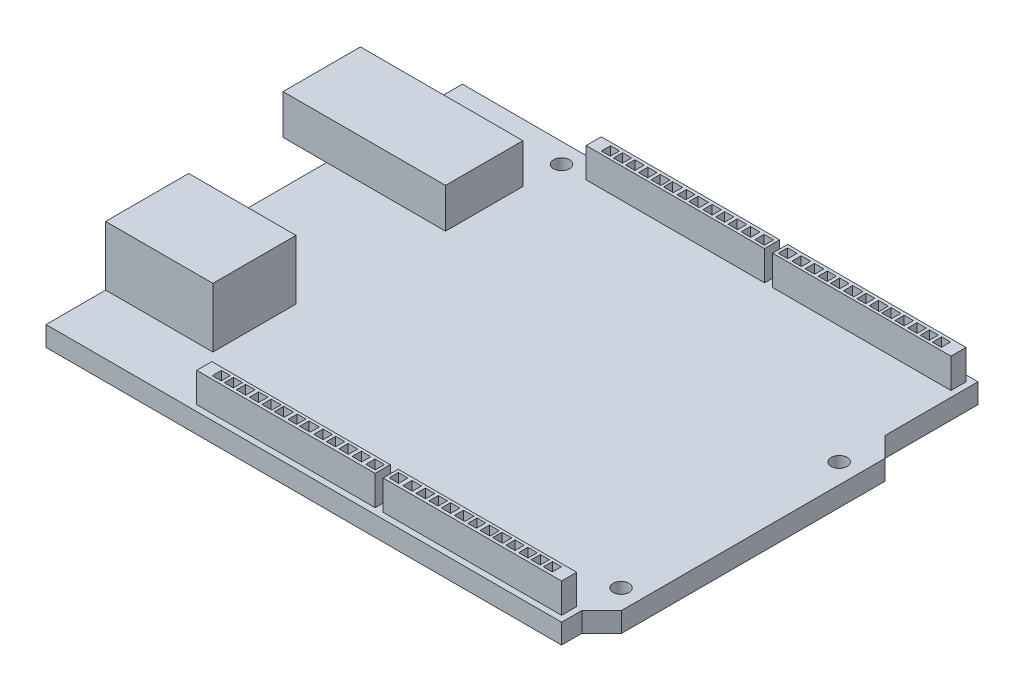
SolidWorks part; units mm, degrees
ref_plane "Front Plane" through (0, 0, 0) normal (0, 0, 1) x (1, 0, 0)
ref_plane "Top Plane" through (0, 0, 0) normal (0, 1, 0) x (1, 0, 0)
ref_plane "Right Plane" through (0, 0, 0) normal (1, 0, 0) x (0, 0, -1)
sketch "Sketch1" plane through (0, 0, 0) normal (0, 1, 0) x (1, 0, 0)
  line L0 (66.04, 53.34) -> (66.04, 0) construction
  line L1 (0, 0) -> (66.04, 0)
  line L2 (0, 0) -> (0, 53.34)
  line L3 (0, 53.34) -> (66.04, 53.34)
  line L4 (68.58, 5.165) -> (68.58, 38.8711)
  line L5 (68.58, 38.8711) -> (66.04, 41.4111)
  line L6 (66.04, 41.4111) -> (66.04, 53.34)
  line L7 (68.58, 5.165) -> (66.04, 2.625)
  line L8 (66.04, 2.625) -> (66.04, 0)
  circle A0 centre (66.04, 7.62) radius 1.016
  circle A1 centre (66.04, 35.56) radius 1.016
  circle A2 centre (15.24, 50.8) radius 1.016
  dimension "D4" = 7.62
  dimension "D6" = 15.24
  dimension "D1" = 53.34
  dimension "D2" = 68.58
  dimension "D3" = 2.54
  dimension "D5" = 35.56
  dimension "D7" = 2.54
extrude "Boss-Extrude1" add sketch "Sketch1" along normal blind 2.54
sketch "Sketch2" plane through (0, 2.54, 0) normal (0, 1, 0) x (1, 0, 0)
  line L0 (41.9079, 53.34) -> (41.9079, 0) construction
  line L1 (66.04, 53.34) -> (0, 53.34) construction
  line L2 (0, 0) -> (66.04, 0) construction
  line L3 (66.04, 41.4111) -> (66.04, 53.34) construction
  line L4 (65.2759, 52.578) -> (42.4159, 52.578)
  line L5 (65.2759, 52.578) -> (65.2759, 50.6415)
  line L6 (65.2759, 50.6415) -> (42.4159, 50.6415)
  line L7 (42.4159, 52.578) -> (42.4159, 50.6415)
  line L8 (41.0237, 50.9966) -> (39.7991, 50.9966)
  line L9 (42.792, 52.1814) -> (44.0166, 52.1814)
  line L10 (42.792, 52.1814) -> (42.792, 50.9966)
  line L11 (42.792, 50.9966) -> (44.0166, 50.9966)
  line L12 (44.0166, 52.1814) -> (44.0166, 50.9966)
  line L13 (44.548, 52.1814) -> (45.7701, 52.1814)
  line L14 (44.548, 52.1814) -> (44.548, 50.9966)
  line L15 (44.548, 50.9966) -> (45.7701, 50.9966)
  line L16 (45.7701, 52.1814) -> (45.7701, 50.9966)
  line L17 (46.2359, 52.1814) -> (47.4586, 52.1814)
  line L18 (46.2359, 52.1814) -> (46.2359, 50.9966)
  line L19 (46.2359, 50.9966) -> (47.4586, 50.9966)
  line L20 (47.4586, 52.1814) -> (47.4586, 50.9966)
  line L21 (47.9019, 52.1814) -> (49.0577, 52.1814)
  line L22 (47.9019, 52.1814) -> (47.9019, 50.9966)
  line L23 (47.9019, 50.9966) -> (49.0577, 50.9966)
  line L24 (49.0577, 52.1814) -> (49.0577, 50.9966)
  line L25 (49.4779, 52.1814) -> (50.6776, 52.1814)
  line L26 (49.4779, 52.1814) -> (49.4779, 50.9966)
  line L27 (49.4779, 50.9966) -> (50.6776, 50.9966)
  line L28 (50.6776, 52.1814) -> (50.6776, 50.9966)
  line L29 (51.1421, 52.1814) -> (52.4761, 52.1814)
  line L30 (51.1421, 52.1814) -> (51.1421, 50.9966)
  line L31 (51.1421, 50.9966) -> (52.4761, 50.9966)
  line L32 (52.4761, 52.1814) -> (52.4761, 50.9966)
  line L33 (52.8762, 52.1814) -> (53.9841, 52.1814)
  line L34 (52.8762, 52.1814) -> (52.8762, 50.9966)
  line L35 (52.8762, 50.9966) -> (53.9841, 50.9966)
  line L36 (53.9841, 52.1814) -> (53.9841, 50.9966)
  line L37 (54.451, 52.1814) -> (55.7188, 52.1814)
  line L38 (54.451, 52.1814) -> (54.451, 50.9966)
  line L39 (54.451, 50.9966) -> (55.7188, 50.9966)
  line L40 (55.7188, 52.1814) -> (55.7188, 50.9966)
  line L41 (56.049, 52.1814) -> (57.3185, 52.1814)
  line L42 (56.049, 52.1814) -> (56.049, 50.9966)
  line L43 (56.049, 50.9966) -> (57.3185, 50.9966)
  line L44 (57.3185, 52.1814) -> (57.3185, 50.9966)
  line L45 (57.7375, 52.1814) -> (58.917, 52.1814)
  line L46 (57.7375, 52.1814) -> (57.7375, 50.9966)
  line L47 (57.7375, 50.9966) -> (58.917, 50.9966)
  line L48 (58.917, 52.1814) -> (58.917, 50.9966)
  line L49 (59.3804, 52.1814) -> (60.5806, 52.1814)
  line L50 (59.3804, 52.1814) -> (59.3804, 50.9966)
  line L51 (59.3804, 50.9966) -> (60.5806, 50.9966)
  line L52 (60.5806, 52.1814) -> (60.5806, 50.9966)
  line L53 (60.9765, 52.1814) -> (62.136, 52.1814)
  line L54 (60.9765, 52.1814) -> (60.9765, 50.9966)
  line L55 (60.9765, 50.9966) -> (62.136, 50.9966)
  line L56 (62.136, 52.1814) -> (62.136, 50.9966)
  line L57 (62.5313, 52.1814) -> (63.6847, 52.1814)
  line L58 (62.5313, 52.1814) -> (62.5313, 50.9966)
  line L59 (62.5313, 50.9966) -> (63.6847, 50.9966)
  line L60 (63.6847, 52.1814) -> (63.6847, 50.9966)
  line L61 (41.0237, 52.1814) -> (41.0237, 50.9966)
  line L62 (41.0237, 52.1814) -> (39.7991, 52.1814)
  line L63 (41.3999, 52.578) -> (41.3999, 50.6415)
  line L64 (18.5399, 50.6415) -> (41.3999, 50.6415)
  line L65 (18.5399, 52.578) -> (41.3999, 52.578)
  line L66 (21.6797, 52.1814) -> (21.6797, 50.9966)
  line L67 (22.8392, 50.9966) -> (21.6797, 50.9966)
  line L68 (22.8392, 52.1814) -> (22.8392, 50.9966)
  line L69 (22.8392, 52.1814) -> (21.6797, 52.1814)
  line L70 (23.2351, 52.1814) -> (23.2351, 50.9966)
  line L71 (24.4353, 50.9966) -> (23.2351, 50.9966)
  line L72 (24.4353, 52.1814) -> (24.4353, 50.9966)
  line L73 (24.4353, 52.1814) -> (23.2351, 52.1814)
  line L74 (24.8987, 52.1814) -> (24.8987, 50.9966)
  line L75 (26.0782, 50.9966) -> (24.8987, 50.9966)
  line L76 (26.0782, 52.1814) -> (26.0782, 50.9966)
  line L77 (26.0782, 52.1814) -> (24.8987, 52.1814)
  line L78 (26.4972, 52.1814) -> (26.4972, 50.9966)
  line L79 (27.7667, 50.9966) -> (26.4972, 50.9966)
  line L80 (27.7667, 52.1814) -> (27.7667, 50.9966)
  line L81 (27.7667, 52.1814) -> (26.4972, 52.1814)
  line L82 (28.097, 52.1814) -> (28.097, 50.9966)
  line L83 (29.3647, 50.9966) -> (28.097, 50.9966)
  line L84 (29.3647, 52.1814) -> (29.3647, 50.9966)
  line L85 (29.3647, 52.1814) -> (28.097, 52.1814)
  line L86 (29.8316, 52.1814) -> (29.8316, 50.9966)
  line L87 (30.9395, 50.9966) -> (29.8316, 50.9966)
  line L88 (30.9395, 52.1814) -> (30.9395, 50.9966)
  line L89 (30.9395, 52.1814) -> (29.8316, 52.1814)
  line L90 (31.3396, 52.1814) -> (31.3396, 50.9966)
  line L91 (32.6736, 50.9966) -> (31.3396, 50.9966)
  line L92 (32.6736, 52.1814) -> (32.6736, 50.9966)
  line L93 (32.6736, 52.1814) -> (31.3396, 52.1814)
  line L94 (33.1381, 52.1814) -> (33.1381, 50.9966)
  line L95 (34.3378, 50.9966) -> (33.1381, 50.9966)
  line L96 (34.3378, 52.1814) -> (34.3378, 50.9966)
  line L97 (34.3378, 52.1814) -> (33.1381, 52.1814)
  line L98 (34.758, 52.1814) -> (34.758, 50.9966)
  line L99 (35.9138, 50.9966) -> (34.758, 50.9966)
  line L100 (35.9138, 52.1814) -> (35.9138, 50.9966)
  line L101 (35.9138, 52.1814) -> (34.758, 52.1814)
  line L102 (36.3571, 52.1814) -> (36.3571, 50.9966)
  line L103 (37.5798, 50.9966) -> (36.3571, 50.9966)
  line L104 (37.5798, 52.1814) -> (37.5798, 50.9966)
  line L105 (37.5798, 52.1814) -> (36.3571, 52.1814)
  line L106 (38.0456, 52.1814) -> (38.0456, 50.9966)
  line L107 (39.2677, 50.9966) -> (38.0456, 50.9966)
  line L108 (39.2677, 52.1814) -> (39.2677, 50.9966)
  line L109 (39.2677, 52.1814) -> (38.0456, 52.1814)
  line L110 (39.7991, 52.1814) -> (39.7991, 50.9966)
  line L111 (18.5399, 52.578) -> (18.5399, 50.6415)
  line L112 (21.2844, 50.9966) -> (20.131, 50.9966)
  line L113 (20.131, 52.1814) -> (20.131, 50.9966)
  line L114 (21.2844, 52.1814) -> (20.131, 52.1814)
  line L115 (21.2844, 52.1814) -> (21.2844, 50.9966)
  line L116 (0, 26.67) -> (68.58, 26.67) construction
  line L117 (0, 53.34) -> (0, 0) construction
  line L118 (68.58, 5.165) -> (68.58, 38.8711) construction
  line L119 (65.2759, 0.762) -> (65.2759, 2.6985)
  line L120 (65.2759, 0.762) -> (42.4159, 0.762)
  line L121 (65.2759, 2.6985) -> (42.4159, 2.6985)
  line L122 (20.131, 1.1586) -> (20.131, 2.3434)
  line L123 (21.2844, 2.3434) -> (20.131, 2.3434)
  line L124 (18.5399, 2.6985) -> (41.3999, 2.6985)
  line L125 (18.5399, 0.762) -> (18.5399, 2.6985)
  line L126 (21.2844, 1.1586) -> (21.2844, 2.3434)
  line L127 (21.2844, 1.1586) -> (20.131, 1.1586)
  line L128 (39.7991, 1.1586) -> (39.7991, 2.3434)
  line L129 (39.2677, 1.1586) -> (38.0456, 1.1586)
  line L130 (39.2677, 1.1586) -> (39.2677, 2.3434)
  line L131 (39.2677, 2.3434) -> (38.0456, 2.3434)
  line L132 (38.0456, 1.1586) -> (38.0456, 2.3434)
  line L133 (37.5798, 1.1586) -> (36.3571, 1.1586)
  line L134 (37.5798, 1.1586) -> (37.5798, 2.3434)
  line L135 (37.5798, 2.3434) -> (36.3571, 2.3434)
  line L136 (36.3571, 1.1586) -> (36.3571, 2.3434)
  line L137 (35.9138, 1.1586) -> (34.758, 1.1586)
  line L138 (35.9138, 1.1586) -> (35.9138, 2.3434)
  line L139 (35.9138, 2.3434) -> (34.758, 2.3434)
  line L140 (34.758, 1.1586) -> (34.758, 2.3434)
  line L141 (34.3378, 1.1586) -> (33.1381, 1.1586)
  line L142 (34.3378, 1.1586) -> (34.3378, 2.3434)
  line L143 (34.3378, 2.3434) -> (33.1381, 2.3434)
  line L144 (33.1381, 1.1586) -> (33.1381, 2.3434)
  line L145 (32.6736, 1.1586) -> (31.3396, 1.1586)
  line L146 (32.6736, 1.1586) -> (32.6736, 2.3434)
  line L147 (32.6736, 2.3434) -> (31.3396, 2.3434)
  line L148 (31.3396, 1.1586) -> (31.3396, 2.3434)
  line L149 (30.9395, 1.1586) -> (29.8316, 1.1586)
  line L150 (30.9395, 1.1586) -> (30.9395, 2.3434)
  line L151 (30.9395, 2.3434) -> (29.8316, 2.3434)
  line L152 (29.8316, 1.1586) -> (29.8316, 2.3434)
  line L153 (29.3647, 1.1586) -> (28.097, 1.1586)
  line L154 (29.3647, 1.1586) -> (29.3647, 2.3434)
  line L155 (29.3647, 2.3434) -> (28.097, 2.3434)
  line L156 (28.097, 1.1586) -> (28.097, 2.3434)
  line L157 (27.7667, 1.1586) -> (26.4972, 1.1586)
  line L158 (27.7667, 1.1586) -> (27.7667, 2.3434)
  line L159 (27.7667, 2.3434) -> (26.4972, 2.3434)
  line L160 (26.4972, 1.1586) -> (26.4972, 2.3434)
  line L161 (26.0782, 1.1586) -> (24.8987, 1.1586)
  line L162 (26.0782, 1.1586) -> (26.0782, 2.3434)
  line L163 (26.0782, 2.3434) -> (24.8987, 2.3434)
  line L164 (24.8987, 1.1586) -> (24.8987, 2.3434)
  line L165 (24.4353, 1.1586) -> (23.2351, 1.1586)
  line L166 (24.4353, 1.1586) -> (24.4353, 2.3434)
  line L167 (24.4353, 2.3434) -> (23.2351, 2.3434)
  line L168 (23.2351, 1.1586) -> (23.2351, 2.3434)
  line L169 (22.8392, 1.1586) -> (21.6797, 1.1586)
  line L170 (22.8392, 1.1586) -> (22.8392, 2.3434)
  line L171 (22.8392, 2.3434) -> (21.6797, 2.3434)
  line L172 (21.6797, 1.1586) -> (21.6797, 2.3434)
  line L173 (18.5399, 0.762) -> (41.3999, 0.762)
  line L174 (41.3999, 0.762) -> (41.3999, 2.6985)
  line L175 (41.0237, 1.1586) -> (39.7991, 1.1586)
  line L176 (41.0237, 1.1586) -> (41.0237, 2.3434)
  line L177 (63.6847, 1.1586) -> (63.6847, 2.3434)
  line L178 (62.5313, 2.3434) -> (63.6847, 2.3434)
  line L179 (62.5313, 1.1586) -> (62.5313, 2.3434)
  line L180 (62.5313, 1.1586) -> (63.6847, 1.1586)
  line L181 (62.136, 1.1586) -> (62.136, 2.3434)
  line L182 (60.9765, 2.3434) -> (62.136, 2.3434)
  line L183 (60.9765, 1.1586) -> (60.9765, 2.3434)
  line L184 (60.9765, 1.1586) -> (62.136, 1.1586)
  line L185 (60.5806, 1.1586) -> (60.5806, 2.3434)
  line L186 (59.3804, 2.3434) -> (60.5806, 2.3434)
  line L187 (59.3804, 1.1586) -> (59.3804, 2.3434)
  line L188 (59.3804, 1.1586) -> (60.5806, 1.1586)
  line L189 (58.917, 1.1586) -> (58.917, 2.3434)
  line L190 (57.7375, 2.3434) -> (58.917, 2.3434)
  line L191 (57.7375, 1.1586) -> (57.7375, 2.3434)
  line L192 (57.7375, 1.1586) -> (58.917, 1.1586)
  line L193 (57.3185, 1.1586) -> (57.3185, 2.3434)
  line L194 (56.049, 2.3434) -> (57.3185, 2.3434)
  line L195 (56.049, 1.1586) -> (56.049, 2.3434)
  line L196 (56.049, 1.1586) -> (57.3185, 1.1586)
  line L197 (55.7188, 1.1586) -> (55.7188, 2.3434)
  line L198 (54.451, 2.3434) -> (55.7188, 2.3434)
  line L199 (54.451, 1.1586) -> (54.451, 2.3434)
  line L200 (54.451, 1.1586) -> (55.7188, 1.1586)
  line L201 (53.9841, 1.1586) -> (53.9841, 2.3434)
  line L202 (52.8762, 2.3434) -> (53.9841, 2.3434)
  line L203 (52.8762, 1.1586) -> (52.8762, 2.3434)
  line L204 (52.8762, 1.1586) -> (53.9841, 1.1586)
  line L205 (52.4761, 1.1586) -> (52.4761, 2.3434)
  line L206 (51.1421, 2.3434) -> (52.4761, 2.3434)
  line L207 (51.1421, 1.1586) -> (51.1421, 2.3434)
  line L208 (51.1421, 1.1586) -> (52.4761, 1.1586)
  line L209 (50.6776, 1.1586) -> (50.6776, 2.3434)
  line L210 (49.4779, 2.3434) -> (50.6776, 2.3434)
  line L211 (49.4779, 1.1586) -> (49.4779, 2.3434)
  line L212 (49.4779, 1.1586) -> (50.6776, 1.1586)
  line L213 (49.0577, 1.1586) -> (49.0577, 2.3434)
  line L214 (47.9019, 2.3434) -> (49.0577, 2.3434)
  line L215 (47.9019, 1.1586) -> (47.9019, 2.3434)
  line L216 (47.9019, 1.1586) -> (49.0577, 1.1586)
  line L217 (47.4586, 1.1586) -> (47.4586, 2.3434)
  line L218 (46.2359, 2.3434) -> (47.4586, 2.3434)
  line L219 (46.2359, 1.1586) -> (46.2359, 2.3434)
  line L220 (46.2359, 1.1586) -> (47.4586, 1.1586)
  line L221 (45.7701, 1.1586) -> (45.7701, 2.3434)
  line L222 (44.548, 2.3434) -> (45.7701, 2.3434)
  line L223 (44.548, 1.1586) -> (44.548, 2.3434)
  line L224 (44.548, 1.1586) -> (45.7701, 1.1586)
  line L225 (44.0166, 1.1586) -> (44.0166, 2.3434)
  line L226 (42.792, 2.3434) -> (44.0166, 2.3434)
  line L227 (42.792, 1.1586) -> (42.792, 2.3434)
  line L228 (42.792, 1.1586) -> (44.0166, 1.1586)
  line L229 (41.0237, 2.3434) -> (39.7991, 2.3434)
  line L230 (42.4159, 0.762) -> (42.4159, 2.6985)
  point P10 (65.2759, 51.6098)
  dimension "D1" = 22.86
  dimension "D2" = 0.7641
  dimension "D3" = 0.508
  dimension "D4" = 0.762
  dimension "D5" = 1.9365
extrude "Boss-Extrude2" add sketch "Sketch2" along normal blind 3.81
sketch "Sketch3" plane through (0, 2.54, 0) normal (0, 1, 0) x (1, 0, 0)
  line L0 (0, 53.34) -> (0, 0) construction
  line L1 (0, 4.997) -> (15.2292, 4.997)
  line L2 (0, 4.997) -> (0, 13.1919)
  line L3 (0, 13.1919) -> (15.2292, 13.1919)
  line L4 (15.2292, 4.997) -> (15.2292, 13.1919)
  line L6 (0, 45.8563) -> (15.2292, 45.8563)
  line L8 (0, 35.9443) -> (15.2292, 35.9443)
  line L9 (15.2292, 45.8563) -> (15.2292, 35.9443)
  line L10 (0, 45.8563) -> (-5.5812, 45.8563)
  line L11 (0, 45.8563) -> (0, 35.9443)
  line L12 (0, 35.9443) -> (-5.5812, 35.9443)
  line L13 (-5.5812, 45.8563) -> (-5.5812, 35.9443)
  line M1 (0, 53.34) -> (0, 0)
extrude "Boss-Extrude3" add sketch "Sketch3" along normal blind 5.08 contours L9 L6 L8 M1 | L10 L13 L12 M1
sketch "Sketch4" plane through (0, 2.54, 0) normal (0, 1, 0) x (1, 0, 0)
  line L0 (0, 35.9443) -> (0, 0) construction
  line L1 (0, 7.6357) -> (13.7394, 7.6357)
  line L2 (0, 7.6357) -> (0, 18.2809)
  line L3 (0, 18.2809) -> (13.7394, 18.2809)
  line L4 (13.7394, 7.6357) -> (13.7394, 18.2809)
extrude "Boss-Extrude4" add sketch "Sketch4" along normal blind 7.62
sketch "Sketch5" plane through (0, 0, 0) normal (-1, 0, 0) x (0, 0, 1)
  line L0 (-18.2809, 6.35) -> (-7.6357, 6.35) construction
  line L1 (-18.2809, 10.16) -> (-18.2809, 2.54) construction
  line L2 (-7.6357, 10.16) -> (-7.6357, 2.54) construction
  circle A0 centre (-12.9583, 6.35) radius 3.3916
extrude "Cut-Extrude1" cut sketch "Sketch5" against normal blind 7.62
sketch "Sketch6" plane through (-5.5812, 0, 0) normal (-1, 0, 0) x (0, 0, 1)
  line L1 (-45.499, 7.2452) -> (-36.3875, 7.2452)
  line L2 (-45.499, 7.2452) -> (-45.499, 2.8904)
  line L3 (-45.499, 2.8904) -> (-36.3875, 2.8904)
  line L4 (-36.3875, 7.2452) -> (-36.3875, 2.8904)
extrude "Cut-Extrude2" cut sketch "Sketch6" against normal blind 15.24
sketch "Sketch7" plane through (9.6588, 0, 0) normal (-1, 0, 0) x (0, 0, 1)
  line L1 (-45.0075, 3.4598) -> (-36.9066, 3.4598)
  line L2 (-45.0075, 3.4598) -> (-45.0075, 5.3009)
  line L3 (-45.0075, 5.3009) -> (-36.9066, 5.3009)
  line L4 (-36.9066, 3.4598) -> (-36.9066, 5.3009)
extrude "Boss-Extrude5" add sketch "Sketch7" along normal blind 13.97
